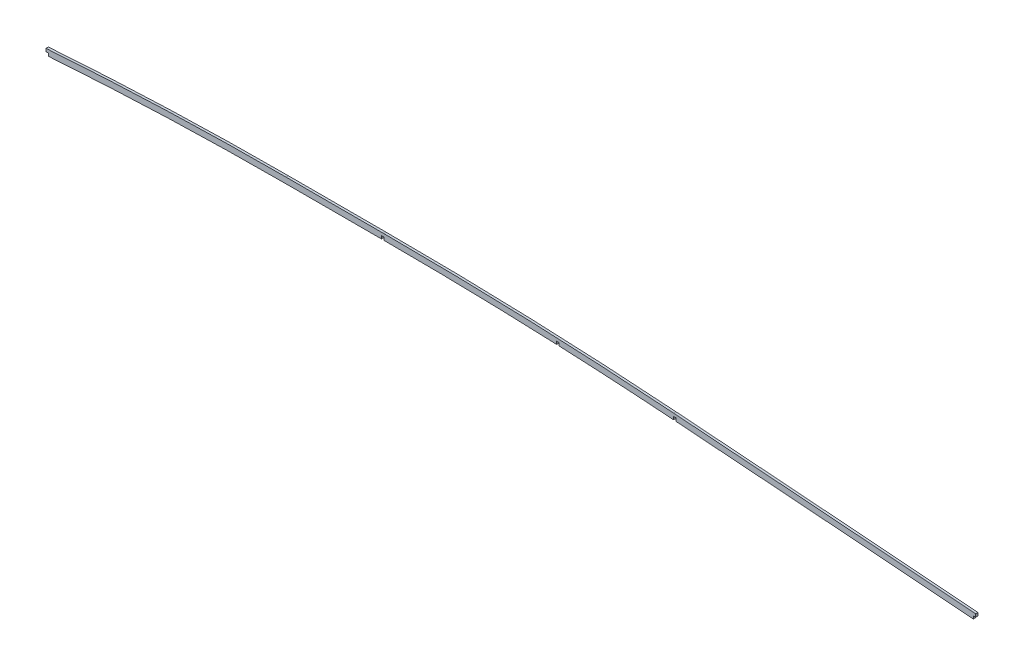
SolidWorks part; units mm, degrees
ref_plane "Front Plane" through (0, 0, 0) normal (0, 0, 1) x (1, 0, 0)
ref_plane "Top Plane" through (0, 0, 0) normal (0, 1, 0) x (1, 0, 0)
ref_plane "Right Plane" through (0, 0, 0) normal (1, 0, 0) x (0, 0, -1)
sketch "Sketch1" plane through (0, 0, 0) normal (0, 0, 1) x (1, 0, 0)
  line L1 (-608.8705, 256.9606) -> (-608.8705, 282.0236)
  line L4 (20.32, -469.9) -> (0, -469.9) construction
  line L5 (418.4703, 293.4483) -> (835.7994, 293.4483)
  line L36 (3391.5497, 148.706) -> (3391.5497, 173.7819)
  line L37 (418.4703, 343.8483) -> (835.7994, 343.8483)
  line L38 (3366.5497, 150.6554) -> (3366.5497, 175.7312)
  line L39 (835.7994, 293.4483) -> (835.7994, 305.9483)
  line L40 (418.4703, 318.4483) -> (835.7994, 318.4483)
  line L41 (-1603.5297, 202.4836) -> (-1599.9954, 177.3306)
  line L42 (3395.4703, 198.9533) -> (3393.4944, 173.6302) construction
  line L43 (-1628.2865, 199.0049) -> (-1621.2706, 149.0738) construction
  line L44 (835.7994, 305.9483) -> (825.7994, 305.9483)
  line L45 (825.7994, 305.9483) -> (825.7994, 293.4483)
  line L46 (2074.7287, 273.2512) -> (2074.7287, 248.1845) construction
  line L47 (2074.7287, 248.1845) -> (2074.7287, 260.6845)
  line L48 (2074.7287, 260.6845) -> (2084.7287, 260.6845)
  line L49 (2084.7287, 260.6845) -> (2084.7287, 247.4537)
  line L50 (3366.5497, 163.1933) -> (3356.5497, 163.1933)
  line L51 (3356.5497, 163.1933) -> (3356.5497, 151.4345)
  line L52 (-608.8705, 269.4921) -> (-598.8705, 269.4921)
  line L53 (-598.8705, 269.4921) -> (-598.8705, 257.6683)
  line L54 (1584.7287, 301.9464) -> (1584.7287, 276.9221)
  line L55 (1584.7287, 289.4343) -> (1574.7287, 289.4343)
  line L56 (1574.7287, 289.4343) -> (1574.7287, 277.3607)
  arc A0 (418.4703, 293.4483) -> (-1621.2706, 149.0738) centre (418.4703, -14187.6006) ccw construction
  arc A1 (2072.907, 248.3176) -> (3391.5497, 148.706) centre (-17442.8336, -266875.6126) cw
  arc A7 (2076.5794, 298.5837) -> (1699.8995, 321.9101) centre (835.7994, -16684.7351) ccw
  arc A8 (1699.8995, 321.9101) -> (1433.1995, 333.366) centre (835.7994, -16684.7351) ccw
  arc A9 (1433.1995, 333.366) -> (835.7994, 343.8483) centre (835.7994, -16684.7351) ccw
  arc A10 (418.4703, 343.8483) -> (-1603.5297, 202.4836) centre (418.4703, -14187.6006) ccw construction
  arc A11 (2076.5794, 298.5837) -> (3395.4703, 198.9533) centre (-17442.8336, -266875.6126) cw construction
  arc A12 (2074.7287, 273.2512) -> (3393.4944, 173.6302) centre (-17442.8336, -266875.6126) cw
  arc A13 (2074.7287, 273.2512) -> (1698.6106, 296.5429) centre (835.7994, -16684.7351) ccw
  arc A14 (1698.6106, 296.5429) -> (1432.3084, 307.9816) centre (835.7994, -16684.7351) ccw
  arc A15 (1432.3084, 307.9816) -> (835.7994, 318.4483) centre (835.7994, -16684.7351) ccw
  arc A16 (418.4703, 318.4483) -> (-1599.9954, 177.3306) centre (418.4703, -14187.6006) ccw
  arc A17 (2072.907, 248.3176) -> (1697.342, 271.5751) centre (835.7994, -16684.7351) ccw
  arc A18 (1697.342, 271.5751) -> (1431.4313, 282.997) centre (835.7994, -16684.7351) ccw
  arc A19 (1431.4313, 282.997) -> (835.7994, 293.4483) centre (835.7994, -16684.7351) ccw
  arc A20 (418.4703, 293.4483) -> (-608.8705, 256.9606) centre (418.4703, -14187.6006) ccw
  dimension "D2" = 4999
  dimension "D1" = 2022
  dimension "D4" = 14531.4488
  dimension "D5" = 267886.2793
  dimension "D6" = 17028.5833
  dimension "D7" = 17028.5833
  dimension "D8" = 417.3291
  dimension "D3" = 1318.8908
  dimension "D10" = 1658.1092
  dimension "D12" = 25
  dimension "D13" = 12.5
  dimension "D14" = 10
  dimension "D15" = 12.5
  dimension "D16" = 10
  dimension "D17" = 10
  dimension "D18" = 10
  dimension "D19" = 490
  dimension "D20" = 10
  dimension "D9" = 25.4
  dimension "D11" = 25
extrude "Boss-Extrude1" add sketch "Sketch1" along normal blind 10 contours A20 L5 A19 A18 A17 A1 L38 A12 A13 A14 A15 L40 A16 L1 | A18 A17 A1 L47 L48 L49 L51 L50 L38 A12 A13 A14 L54
